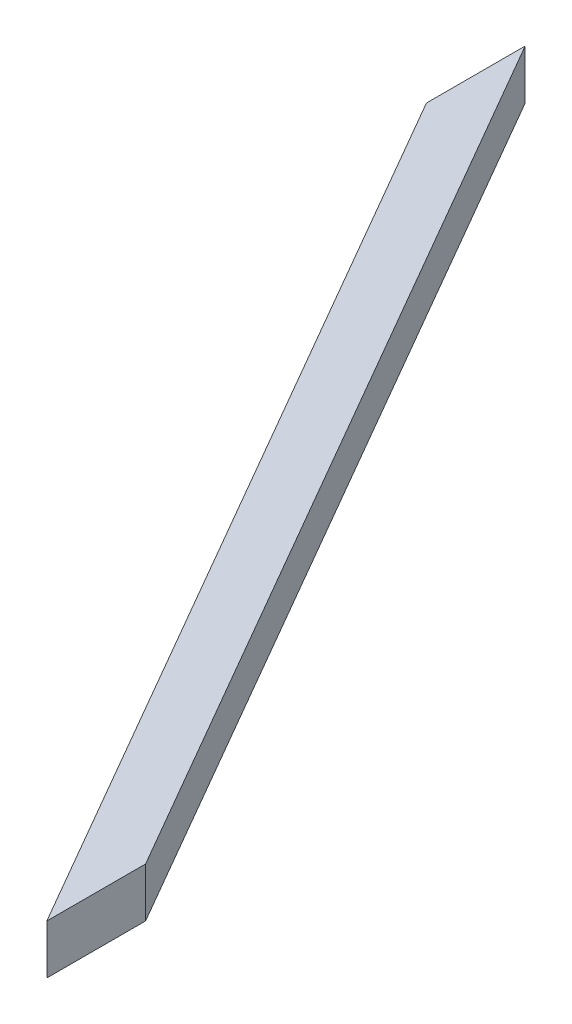
SolidWorks part; units mm, degrees
ref_plane "前视基准面" through (0, 0, 0) normal (0, 0, 1) x (1, 0, 0)
ref_plane "上视基准面" through (0, 0, 0) normal (0, 1, 0) x (1, 0, 0)
ref_plane "右视基准面" through (0, 0, 0) normal (1, 0, 0) x (0, 0, -1)
sketch "草图1" plane through (0, 0, 0) normal (0, 1, 0) x (1, 0, 0)
  line L1 (-600, -200) -> (-159.174, -200) construction
  line L2 (-600, -200) -> (-600, -238.9513) construction
  line L3 (-41.2343, -240) -> (600, -240) construction
  line L4 (600, -200) -> (600, -240) construction
  line L5 (-100, -223.0398) -> (600, -240) construction
  line L6 (-100, -229.7065) -> (600, -200) construction
  line L7 (110, -603.7307) -> (110, -563.7307)
  line L8 (110, -563.7307) -> (-100, -200)
  line L10 (-100, -200) -> (-100, -240)
  line L11 (-100, -200) -> (600, -200) construction
  line L12 (-100, -240) -> (110, -603.7307)
  point P0 (0, -225.4627)
  point P7 (0, 0)
  point P12 (0, 0)
  point P13 (0, 0)
  dimension "D1" = 1200
  dimension "D2" = 200
  dimension "D3" = 20
  dimension "D4" = 60
  dimension "D5" = 420
  dimension "D6" = 500
  dimension "D7" = 600
extrude "凸台-拉伸1" add sketch "草图1" along normal blind 20
